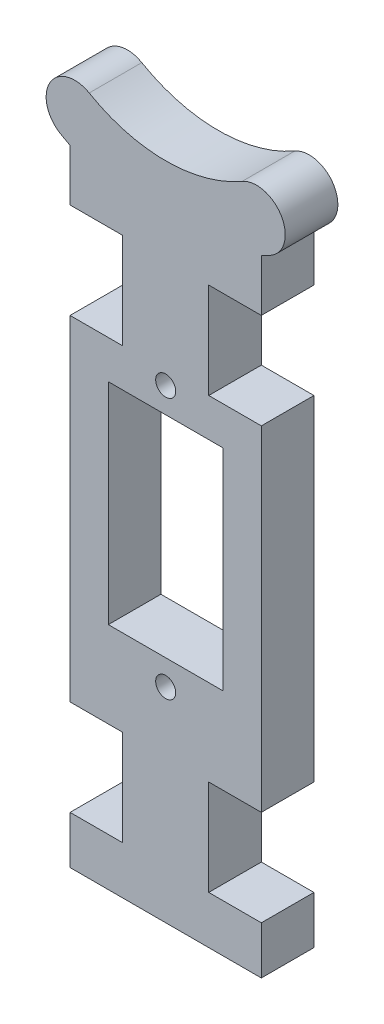
SolidWorks part; units mm, degrees
material "ﾁｰｸ材"
ref_plane "正面" through (0, 0, 0) normal (0, 0, 1) x (1, 0, 0)
ref_plane "平面" through (0, 0, 0) normal (0, 1, 0) x (1, 0, 0)
ref_plane "右側面" through (0, 0, 0) normal (1, 0, 0) x (0, 0, -1)
sketch "ｽｹｯﾁ1" plane through (0, 0, 0) normal (0, 0, 1) x (1, 0, 0)
  line L0 (-10, -19.5959) -> (-10, -85)
  line L1 (-10, -85) -> (10, -85)
  line L2 (10, -85) -> (10, -19.5959)
  arc A0 (-8, -13.8564) -> (8, -13.8564) centre (0, 0) ccw
  arc A1 (8, -13.8564) -> (11, -19.0526) centre (9.5, -16.4545) cw
  arc A2 (11, -19.0526) -> (10, -19.5959) centre (0, 0) cw
  arc A3 (-11, -19.0526) -> (-8, -13.8564) centre (-9.5, -16.4545) cw
  arc A4 (-10, -19.5959) -> (-11, -19.0526) centre (0, 0) cw
  point P9 (0, -85)
  dimension "D1" = 16
  dimension "D2" = 22
  dimension "D3" = 60
  dimension "D5" = 20
  dimension "D4" = 85
extrude "ﾎﾞｽ - 押し出し1" add sketch "ｽｹｯﾁ1" along normal blind 5.5
sketch "ｽｹｯﾁ2" plane through (0, 0, 5.5) normal (0, 0, 1) x (1, 0, 0)
  line L18 (-10, -19.5959) -> (-10, -85) construction
  line L59 (-10, -80) -> (-4.5, -80)
  line L60 (-10, -80) -> (-10, -70)
  line L61 (-10, -70) -> (-4.5, -70)
  line L62 (-4.5, -80) -> (-4.5, -70)
  line L63 (-10, -85) -> (10, -85) construction
  line L66 (-10, -35) -> (-10, -25)
  line L67 (-10, -35) -> (-4.5, -35)
  line L68 (-4.5, -35) -> (-4.5, -25)
  line L69 (-10, -25) -> (-4.5, -25)
  line L78 (0, 0) -> (0, -11.9682) construction
  line L79 (10, -70) -> (4.5, -70)
  line L80 (4.5, -80) -> (4.5, -70)
  line L81 (10, -80) -> (4.5, -80)
  line L82 (10, -80) -> (10, -70)
  line L87 (10, -35) -> (4.5, -35)
  line L88 (4.5, -35) -> (4.5, -25)
  line L89 (10, -25) -> (4.5, -25)
  line L90 (10, -35) -> (10, -25)
  line L99 (-10, 10) -> (-10, 20) [skipped]
  line L100 (-10, 20) -> (-4.5, 20) [skipped]
  line L101 (-4.5, 10) -> (-4.5, 20) [skipped]
  line L102 (-10, 10) -> (-4.5, 10) [skipped]
  line L103 (-10, -12.5) -> (-10, -2.5) [skipped]
  line L104 (-10, -2.5) -> (-4.5, -2.5) [skipped]
  line L105 (-4.5, -12.5) -> (-4.5, -2.5) [skipped]
  line L106 (-10, -12.5) -> (-4.5, -12.5) [skipped]
  line L107 (-10, -57.5) -> (-10, -47.5) [skipped]
  line L108 (-10, -47.5) -> (-4.5, -47.5) [skipped]
  line L109 (-4.5, -57.5) -> (-4.5, -47.5) [skipped]
  line L110 (-10, -57.5) -> (-4.5, -57.5) [skipped]
  dimension "D1" = 5.5
  dimension "D2" = 10
  dimension "D3" = 5
  dimension "D5" = 35
  dimension "D4" = 5
sketch "ｽｹｯﾁ3" plane through (0, 0, 5.5) normal (0, 0, 1) x (1, 0, 0)
  line L1 (-6, -39) -> (6, -39)
  line L2 (-6, -39) -> (-6, -61)
  line L3 (-6, -61) -> (6, -61)
  line L4 (6, -39) -> (6, -61)
  line L5 (-6, -39) -> (6, -61) construction
  line L6 (-6, -61) -> (6, -39) construction
  circle A0 centre (0, -36.35) radius 1.05
  circle A1 centre (0, -63.65) radius 1.05
  point P0 (0, -50)
  dimension "D3" = 2.1
  dimension "D5" = 50
  dimension "D1" = 12
  dimension "D2" = 22
  dimension "D4" = 2.65
  dimension "D6" = 2.65
extrude "ｶｯﾄ - 押し出し2" cut sketch "ｽｹｯﾁ3" against normal through all
extrude "ｶｯﾄ - 押し出し3" cut sketch "ｽｹｯﾁ2" against normal through all
